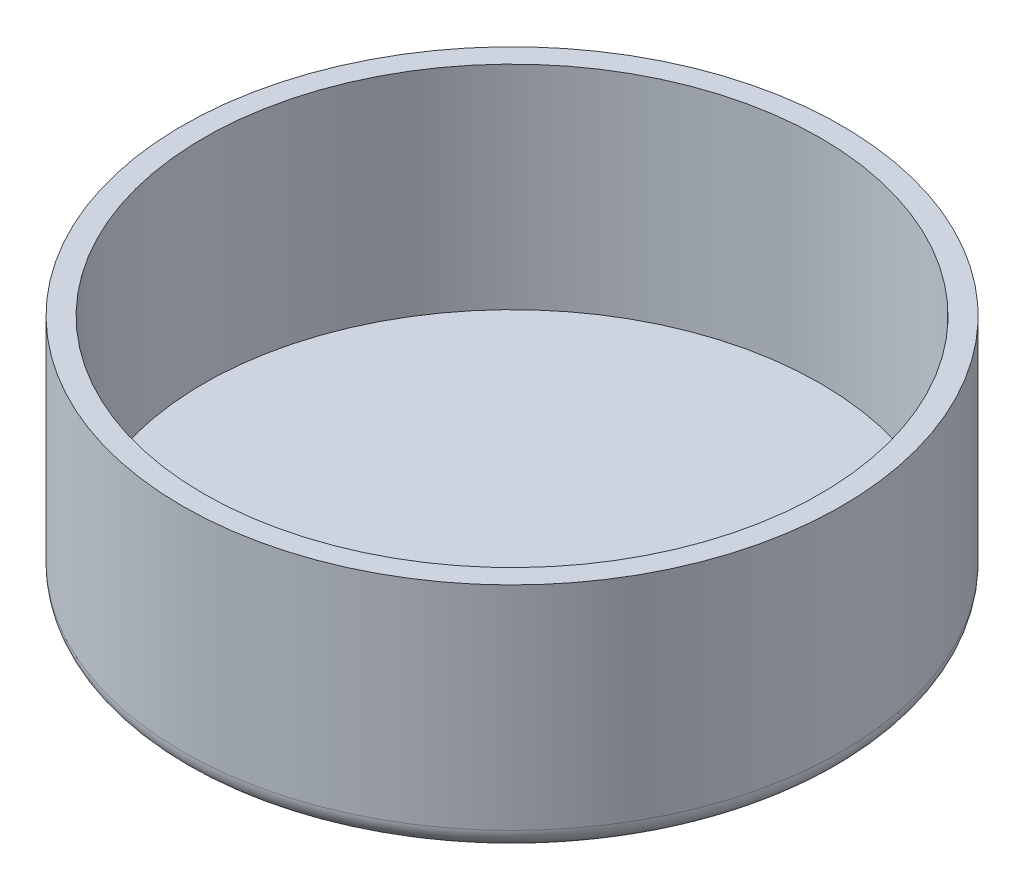
SolidWorks part; units mm, degrees
ref_plane "Front Plane" through (0, 0, 0) normal (0, 0, 1) x (1, 0, 0)
ref_plane "Top Plane" through (0, 0, 0) normal (0, 1, 0) x (1, 0, 0)
ref_plane "Right Plane" through (0, 0, 0) normal (1, 0, 0) x (0, 0, -1)
sketch "Sketch1" plane through (0, 0, 0) normal (0, 1, 0) x (1, 0, 0)
  circle A0 centre (0, 0) radius 15.5
  dimension "D1" = 31
extrude "Boss-Extrude1" add sketch "Sketch1" along normal blind 1
sketch "Sketch3" plane through (0, 1, 0) normal (0, 1, 0) x (1, 0, 0)
  circle A0 centre (0, 0) radius 14.5
  circle A1 centre (0, 0) radius 15.5
  circle A2 centre (0, 0) radius 15.5
  dimension "D1" = 0
  dimension "D2" = 1
extrude "Boss-Extrude2" add sketch "Sketch3" along normal blind 10
fillet "Fillet1" radius 1 1 edges at (0, 0, 15.5)
